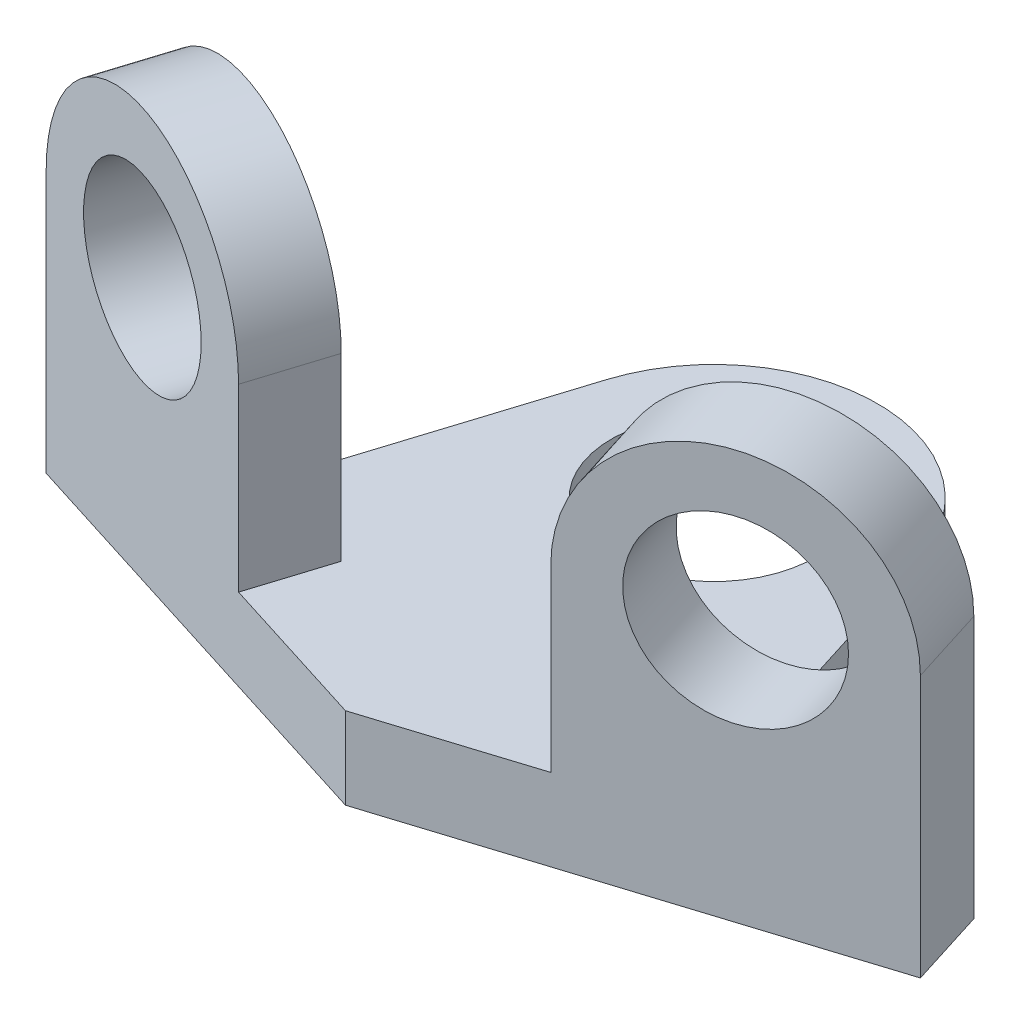
SolidWorks part; units mm, degrees
ref_plane "Płaszczyzna przednia" through (0, 0, 0) normal (0, 0, 1) x (1, 0, 0)
ref_plane "Płaszczyzna górna" through (0, 0, 0) normal (0, 1, 0) x (1, 0, 0)
ref_plane "Płaszczyzna prawa" through (0, 0, 0) normal (1, 0, 0) x (0, 0, -1)
sketch "Szkic3" plane through (0, 0, 0) normal (0, 1, 0) x (1, 0, 0)
  line L0 (0, 0) -> (31.9798, 10.0832)
  line L1 (31.9798, 10.0832) -> (19.0743, 51.0141)
  line L2 (-19.0743, 51.0141) -> (-31.9798, 10.0832)
  line L3 (-31.9798, 10.0832) -> (0, 0)
  line L4 (0, 0) -> (0, 45) construction
  arc A0 (19.0743, 51.0141) -> (-19.0743, 51.0141) centre (0, 45) ccw
  circle A1 centre (0, 45) radius 12.5
  dimension "D2" = 20
  dimension "D3" = 25
  dimension "D1" = 45
  dimension "D4" = 35
extrude "Dodanie-wyciągnięcie1" add sketch "Szkic3" along normal blind 10
sketch "Szkic4" plane through (0, 0, 0) normal (0.3007, 0, 0.9537) x (0.9537, 0, -0.3007)
  line L0 (20, 0) -> (56, 0)
  line L1 (0, 0) -> (33.5318, 0) construction
  line L2 (56, 0) -> (56, 32)
  line L3 (20, 32) -> (20, 0)
  arc A0 (56, 32) -> (20, 32) centre (38, 32) ccw
  circle A1 centre (38, 32) radius 11
  point P11 (0, 0)
  point P12 (0, 0)
  point P13 (0, 0)
  dimension "D2" = 22
  dimension "D3" = 18
  dimension "D1" = 20
  dimension "D4" = 32
extrude "Dodanie-wyciągnięcie2" add sketch "Szkic4" against normal blind 10
sketch "Szkic5" plane through (0, 0, 0) normal (-0.3007, 0, 0.9537) x (0.9537, 0, 0.3007)
  line L0 (-20, 0) -> (-56, 0)
  line L1 (-33.5318, 0) -> (0, 0) construction
  line L2 (-56, 0) -> (-56, 32)
  line L3 (-20, 32) -> (-20, 0)
  arc A0 (-56, 32) -> (-20, 32) centre (-38, 32) cw
  circle A1 centre (-38, 32) radius 11
  point P10 (0, 0)
  point P11 (0, 0)
  dimension "D2" = 18
  dimension "D3" = 22
  dimension "D1" = 20
  dimension "D4" = 32
extrude "Dodanie-wyciągnięcie3" add sketch "Szkic5" against normal blind 10
